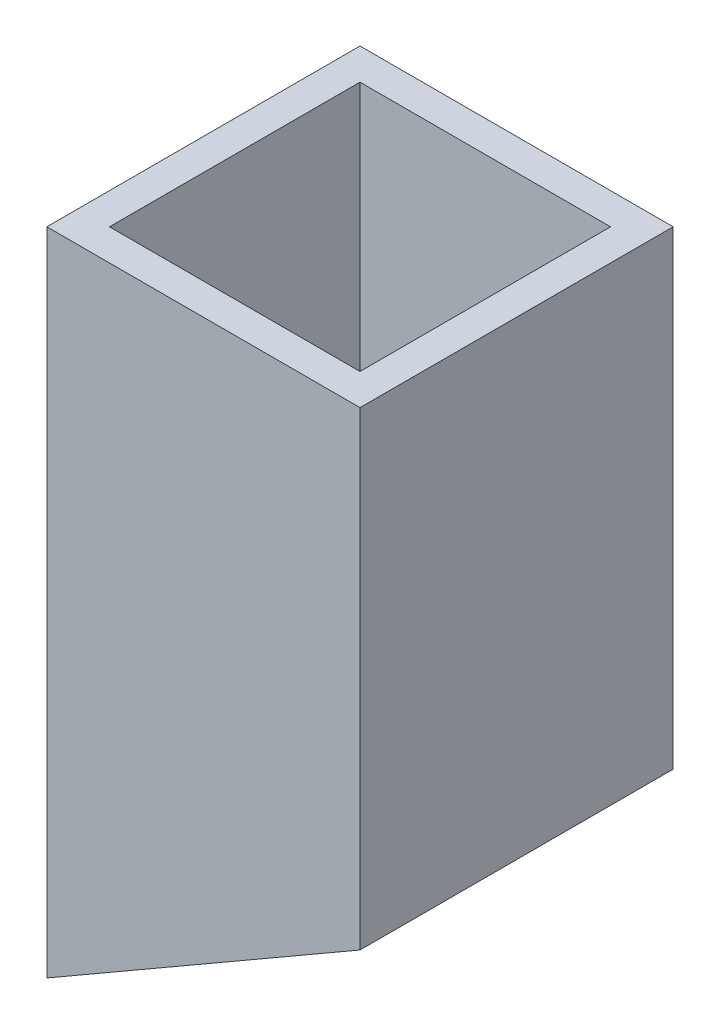
SolidWorks part; units mm, degrees
ref_plane "Alzado" through (0, 0, 0) normal (0, 0, 1) x (1, 0, 0)
ref_plane "Planta" through (0, 0, 0) normal (0, 1, 0) x (1, 0, 0)
ref_plane "Vista lateral" through (0, 0, 0) normal (1, 0, 0) x (0, 0, -1)
sketch "Croquis1" plane through (0, 0, 0) normal (0, 1, 0) x (1, 0, 0)
  line L1 (0, 0) -> (100, 0)
  line L2 (0, 0) -> (0, 100)
  line L3 (0, 100) -> (100, 100)
  line L4 (100, 0) -> (100, 100)
  dimension "D1" = 100
  dimension "D2" = 100
extrude "Saliente-Extruir1" add sketch "Croquis1" along normal blind 150
sketch "Croquis2" plane through (0, 0, 0) normal (0, 0, 1) x (1, 0, 0)
  line L0 (0, 0) -> (0, -57.735)
  line L1 (0, -57.735) -> (100, 0)
  line L2 (100, 0) -> (0, 0)
  dimension "D1" = 30
extrude "Saliente-Extruir2" add sketch "Croquis2" against normal up to surface (100 mm away) up to face at (50, 75, -100)
shell "Vaciado4" thickness 10
